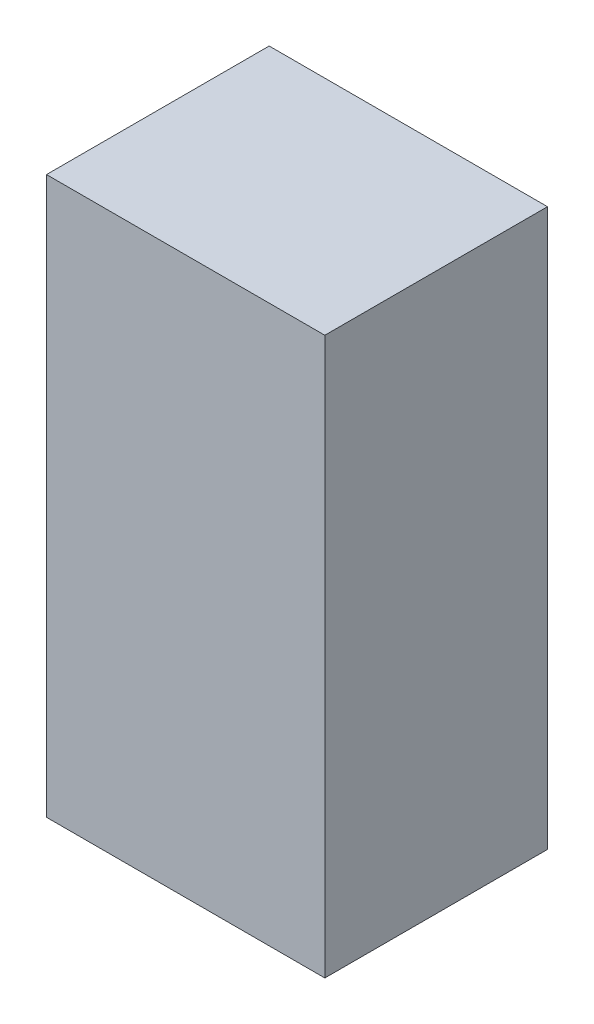
SolidWorks part; units mm, degrees
ref_plane "Front Plane" through (0, 0, 0) normal (0, 0, 1) x (1, 0, 0)
ref_plane "Top Plane" through (0, 0, 0) normal (0, 1, 0) x (1, 0, 0)
ref_plane "Right Plane" through (0, 0, 0) normal (1, 0, 0) x (0, 0, -1)
sketch "Sketch1" plane through (0, 0, 0) normal (1, 0, 0) x (0, 0, -1)
  line L5 (-5, -12.5) -> (5, -12.5)
  line L6 (-5, -12.5) -> (-5, 12.5)
  line L7 (-5, 12.5) -> (5, 12.5)
  line L8 (5, -12.5) -> (5, 12.5)
  line L9 (-5, -12.5) -> (5, 12.5) construction
  line L10 (-5, 12.5) -> (5, -12.5) construction
  point P0 (0, 0)
  dimension "D1" = 25
  dimension "D2" = 10
extrude "Boss-Extrude1" add sketch "Sketch1" along normal blind 12.5
